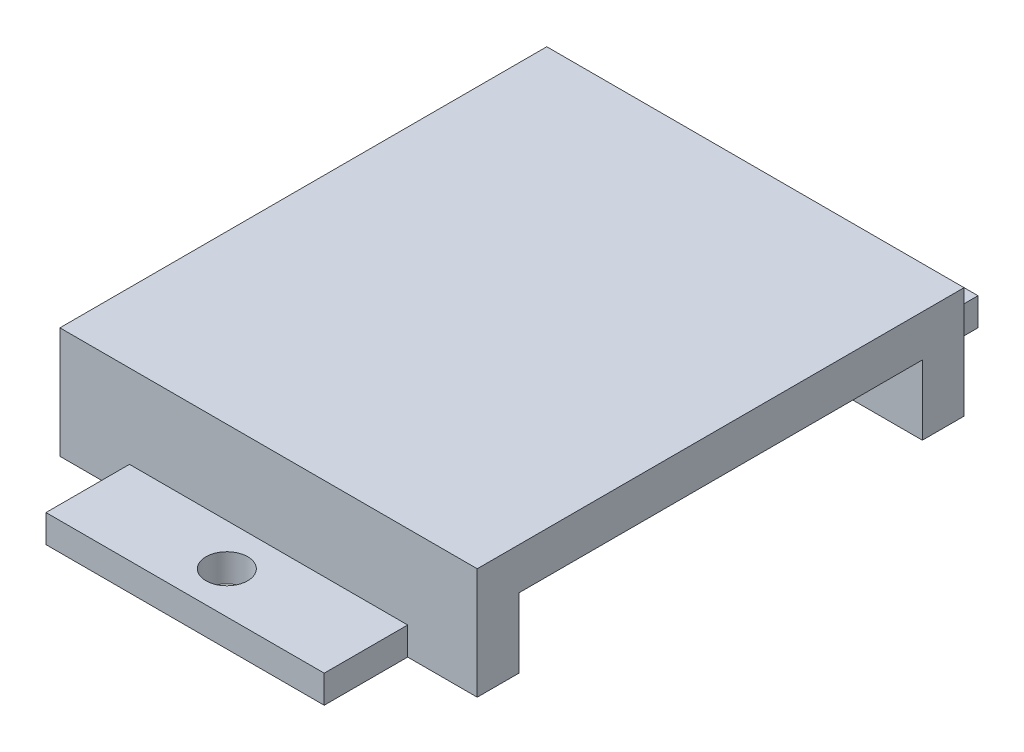
SolidWorks part; units mm, degrees
material "1060 Alloy"
ref_plane "Front Plane" through (0, 0, 0) normal (0, 0, 1) x (1, 0, 0)
ref_plane "Top Plane" through (0, 0, 0) normal (0, 1, 0) x (1, 0, 0)
ref_plane "Right Plane" through (0, 0, 0) normal (1, 0, 0) x (0, 0, -1)
sketch "Sketch1" plane through (0, 0, 0) normal (0, 1, 0) x (1, 0, 0)
  line L1 (0, 0) -> (-30, 0)
  line L2 (0, 0) -> (0, 35)
  line L3 (0, 35) -> (-30, 35)
  line L4 (-30, 0) -> (-30, 35)
  dimension "D1" = 35
  dimension "D2" = 30
extrude "Boss-Extrude1" add sketch "Sketch1" along normal blind 8
sketch "Sketch3" plane through (0, 0, 0) normal (1, 0, 0) x (0, 0, -1)
  line L0 (0, 0) -> (35, 0) construction
  line L1 (3, 0) -> (32, 0)
  line L2 (3, 0) -> (3, 5)
  line L3 (3, 5) -> (32, 5)
  line L4 (32, 0) -> (32, 5)
  line L5 (17.5, 8) -> (17.5, 0) construction
  line L6 (0, 8) -> (35, 8) construction
  point P10 (17.5, 5)
  dimension "D1" = 5
  dimension "D2" = 29
extrude "Cut-Extrude1" cut sketch "Sketch3" against normal blind 68
sketch "Sketch4" plane through (0, 0, 0) normal (0, 0, 1) x (1, 0, 0)
  line L0 (-30, 0) -> (0, 0) construction
  line L1 (-25, 0) -> (-5, 0)
  line L2 (-25, 0) -> (-25, 2)
  line L3 (-25, 2) -> (-5, 2)
  line L4 (-5, 0) -> (-5, 2)
  line L5 (-30, 8) -> (-30, 0) construction
  dimension "D1" = 2
  dimension "D2" = 20
  dimension ".5" = 5
extrude "Boss-Extrude2" add sketch "Sketch4" along normal blind 6
sketch "Sketch5" plane through (0, 0, -35) normal (0, 0, -1) x (-1, 0, 0)
  line L0 (0, 0) -> (30, 0) construction
  line L1 (5, 0) -> (25, 0)
  line L2 (5, 0) -> (5, 2)
  line L3 (5, 2) -> (25, 2)
  line L4 (25, 0) -> (25, 2)
  line L5 (0, 8) -> (0, 0) construction
  dimension "D1" = 2
  dimension "D2" = 20
  dimension "D3" = 5
extrude "Boss-Extrude3" add sketch "Sketch5" along normal blind 6
sketch "Sketch6" plane through (0, 0, 0) normal (0, -1, 0) x (1, 0, 0)
  line L0 (-25, 0) -> (-5, 6) construction
  line L1 (-25, -41) -> (-5, -35) construction
  point P8 (-15, 3)
  point P9 (-15, -38)
hole_wizard "Ø3.0mm Dowel Hole1" positions "Sketch6" profile "Sketch7" hole size "Ø3.0" standard "ANSI Metric"
sketch "Sketch7" plane through (-15, 0, -38) normal (1, 0, 0) x (0, 0, -1)
  line L0 (0, 0) -> (0, 12.9013)
  line L1 (0, 12.9013) -> (1.5, 12)
  line L2 (1.5, 12) -> (1.5, 0)
  line L5 (1.5, 0) -> (0, 0)
  line L10 (0, 12.9013) -> (-1.5, 12) construction
  line L11 (0, -6.35) -> (0, 107.95) construction
  dimension "Hole Dia." = 3
  dimension "Hole Depth" = 12
  dimension "Drill Angle" = 118
